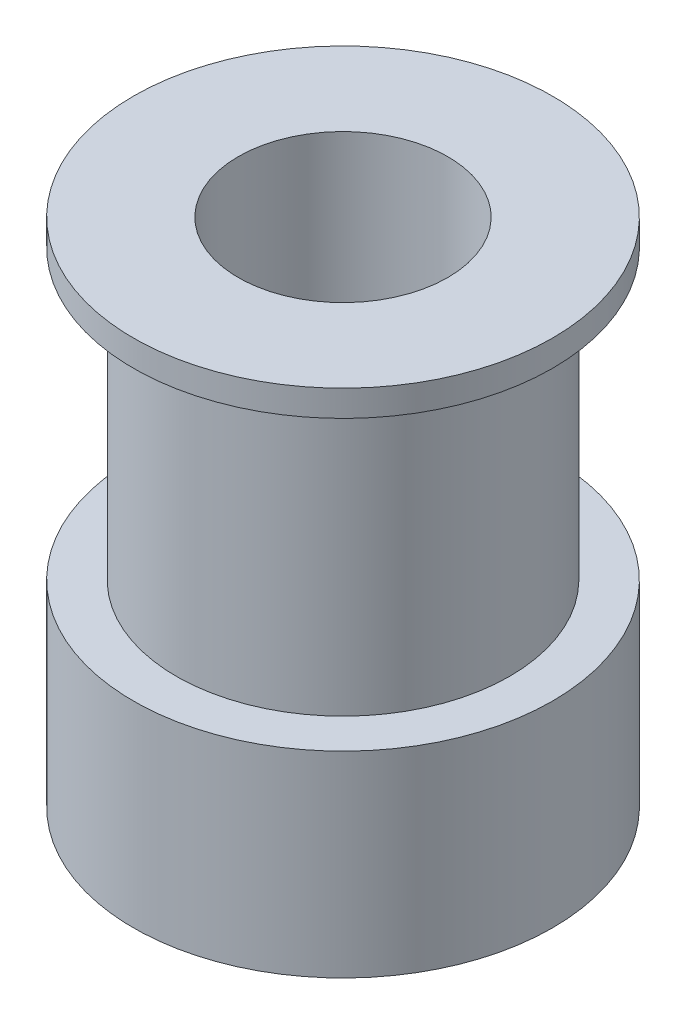
SolidWorks part; units mm, degrees
ref_plane "Спереди" through (0, 0, 0) normal (0, 0, 1) x (1, 0, 0)
ref_plane "Сверху" through (0, 0, 0) normal (0, 1, 0) x (1, 0, 0)
ref_plane "Справа" through (0, 0, 0) normal (1, 0, 0) x (0, 0, -1)
sketch "Эскиз1" plane through (0, 0, 0) normal (0, 0, 1) x (1, 0, 0)
  line L0 (4, 19.5) -> (4, 0)
  line L1 (4, 0) -> (8, 0)
  line L3 (4, 19.5) -> (8, 19.5)
  line L4 (8, 0) -> (8, 19.5)
  line L5 (0, -1000) -> (0, 49000) construction
  line L6 (8, 18.5) -> (6.365, 18.5)
  line L7 (8, 18.5) -> (8, 7.5)
  line L8 (8, 7.5) -> (6.365, 7.5)
  line L9 (6.365, 18.5) -> (6.365, 7.5)
  dimension "D1" = 19.5
  dimension "D2" = 4
  dimension "D3" = 8
  dimension "D4" = 11
  dimension "D5" = 1
  dimension "D6" = 6.365
revolve "Повернуть1" add sketch "Эскиз1" angle 360 about L5
sketch "Эскиз2" plane through (0, 0, 0) normal (0, 0, 1) x (1, 0, 0)
  line L0 (-8, 0) -> (8, 0) construction
  circle A0 centre (0, 3.5) radius 1.5
  point P2 (0, 0)
  dimension "D1" = 3
  dimension "D2" = 3.5
extrude "Вырез-Вытянуть1" cut sketch "Эскиз2" against normal blind 10
ref_plane "Плоскость4" through (0, 13, 0) normal (0, -1, 0) x (-1, 0, 0)
